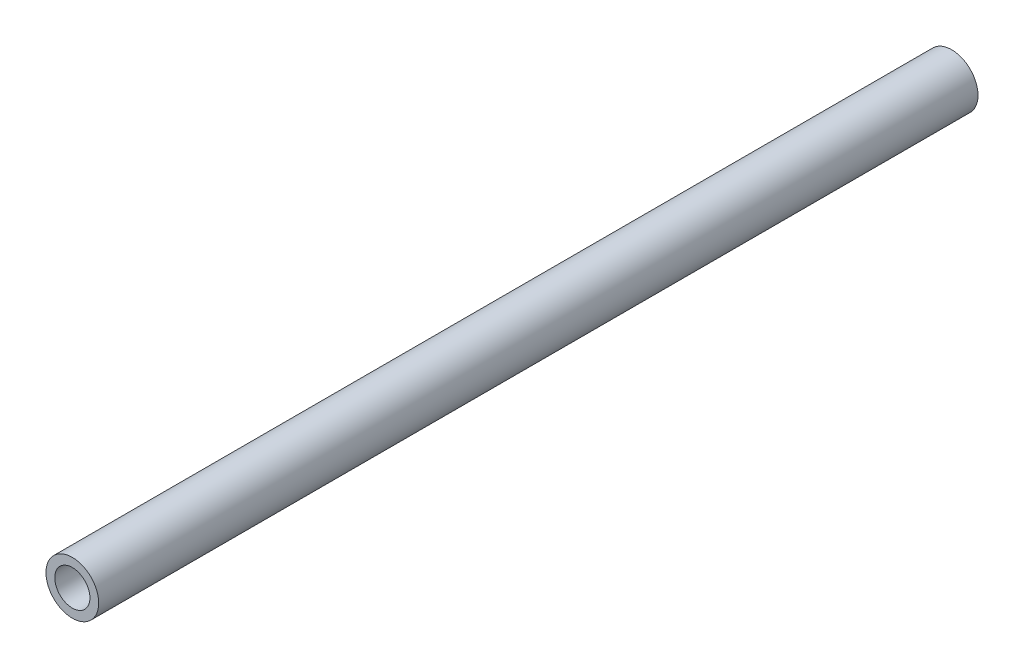
SolidWorks part; units mm, degrees
ref_plane "Front Plane" through (0, 0, 0) normal (0, 0, 1) x (1, 0, 0)
ref_plane "Top Plane" through (0, 0, 0) normal (0, 1, 0) x (1, 0, 0)
ref_plane "Right Plane" through (0, 0, 0) normal (1, 0, 0) x (0, 0, -1)
sketch "Sketch1" plane through (0, 0, 0) normal (0, 0, 1) x (1, 0, 0)
  circle A0 centre (0, 0) radius 3
  circle A1 centre (0, 0) radius 2
  dimension "D1" = 6
  dimension "D2" = 4
extrude "Boss-Extrude1" add sketch "Sketch1" along normal blind 100
